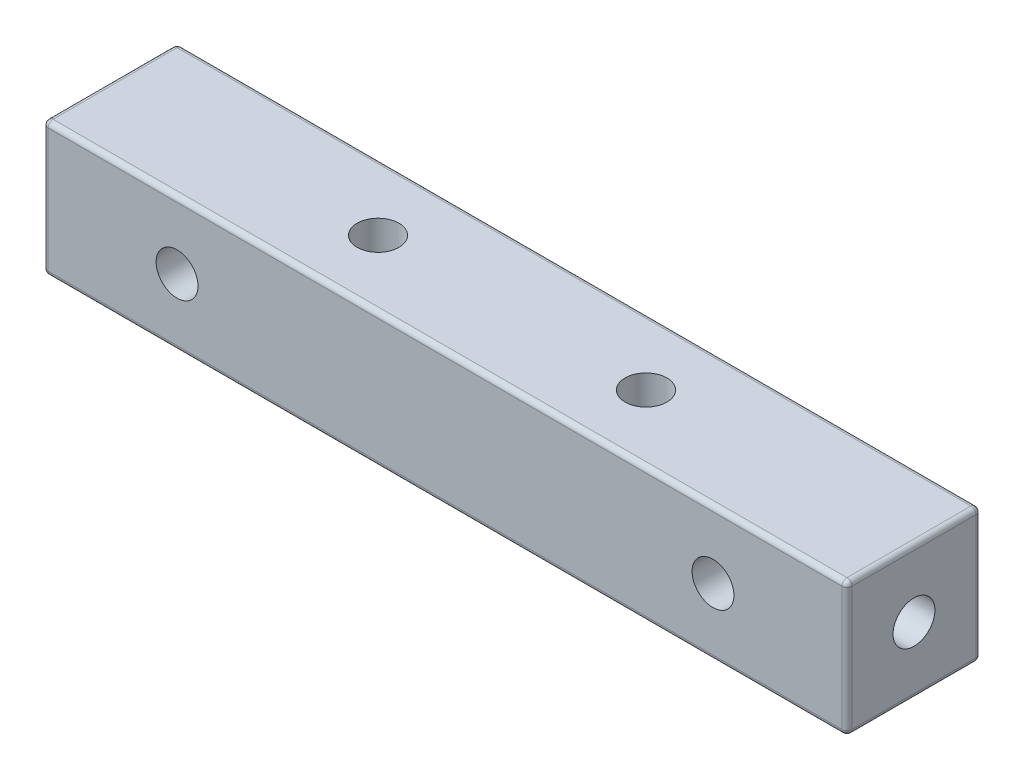
SolidWorks part; units mm, degrees
material "6061 合金"
ref_plane "前视基准面" through (0, 0, 0) normal (0, 0, 1) x (1, 0, 0)
ref_plane "上视基准面" through (0, 0, 0) normal (0, 1, 0) x (1, 0, 0)
ref_plane "右视基准面" through (0, 0, 0) normal (1, 0, 0) x (0, 0, -1)
sketch "草图1" plane through (0, 0, 0) normal (1, 0, 0) x (0, 0, -1)
  line L1 (-4, -4) -> (4, -4)
  line L2 (-4, -4) -> (-4, 4)
  line L3 (-4, 4) -> (4, 4)
  line L4 (4, -4) -> (4, 4)
  line L5 (0, 4) -> (0, -4) construction
  line L6 (-4, 0) -> (4, 0) construction
  point P0 (0, 0)
  dimension "D1" = 8
extrude "凸台-拉伸1" add sketch "草图1" along normal mid plane 48
sketch "草图2" plane through (0, 4, 0) normal (0, 1, 0) x (1, 0, 0)
  line L0 (-8, 0) -> (8, 0) construction
  circle A0 centre (8, 0) radius 1.25
  circle A1 centre (-8, 0) radius 1.25
  point P4 (0, 0)
  dimension "D2" = 2.5
  dimension "D1" = 16
sketch "草图3" plane through (0, 0, 4) normal (0, 0, 1) x (1, 0, 0)
  line L0 (-16, 0) -> (16, 0) construction
  circle A0 centre (16, 0) radius 1.25
  circle A1 centre (-16, 0) radius 1.25
  point P4 (0, 0)
  dimension "D2" = 2.5
  dimension "D1" = 32
sketch "草图4" plane through (24, 0, 0) normal (1, 0, 0) x (0, 0, -1)
  circle A0 centre (0, 0) radius 1.25
  dimension "D1" = 2.5
fillet "圆角1" radius 0.3 12 edges at (-24, -4, 0) (-24, 4, 0) (24, -4, 0) (24, 4, 0) (-24, 0, 4) (-24, 0, -4) (24, 0, -4) (24, 0, 4) (0, -4, -4) (0, 4, -4) (0, -4, 4) (0, 4, 4)
hole_wizard "螺纹孔1" positions "草图5" profile "草图6" tap size "M3" standard "GB" end condition through all
sketch "草图5" plane through (0, 4, 0) normal (0, 1, 0) x (1, 0, 0)
  point P0 (-8, 0)
  point P3 (8, 0)
sketch "草图6" plane through (-8, 4, 0) normal (1, 0, 0) x (0, 0, 1)
  line L0 (0, 0) -> (0, 8)
  line L1 (0, 8) -> (1.25, 8)
  line L2 (1.25, 8) -> (1.25, 0)
  line L5 (1.25, 0) -> (0, 0)
  line L11 (0, -6.35) -> (0, 107.95) construction
  dimension "通孔螺纹孔钻头直径" = 2.5
  dimension "通孔螺纹孔钻头深度" = 8
cosmetic thread "孔螺蚊线1" parameters "D2"=3.6
cosmetic thread "孔螺蚊线2" parameters "D2"=3.6
hole_wizard "螺纹孔2" positions "草图7" profile "草图8" tap size "M3" standard "GB" end condition through all
sketch "草图7" plane through (0, 0, 4) normal (0, 0, 1) x (1, 0, 0)
  point P0 (-16, 0)
  point P3 (16, 0)
sketch "草图8" plane through (-16, 0, 4) normal (1, 0, 0) x (0, -1, 0)
  line L0 (0, 0) -> (0, 8)
  line L1 (0, 8) -> (1.25, 8)
  line L2 (1.25, 8) -> (1.25, 0)
  line L5 (1.25, 0) -> (0, 0)
  line L11 (0, -6.35) -> (0, 107.95) construction
  dimension "通孔螺纹孔钻头直径" = 2.5
  dimension "通孔螺纹孔钻头深度" = 8
cosmetic thread "孔螺蚊线3" parameters "D2"=3.6
cosmetic thread "孔螺蚊线4" parameters "D2"=3.6
hole_wizard "螺纹孔3" positions "草图9" profile "草图10" tap size "M3" standard "GB"
sketch "草图9" plane through (-24, 0, 0) normal (-1, 0, 0) x (0, 0, 1)
  point P0 (0, 0)
sketch "草图10" plane through (-24, 0, 0) normal (0, 1, 0) x (0, 0, 1)
  line L0 (0, 0) -> (0, 6.75)
  line L1 (0, 6.75) -> (1.25, 6.75)
  line L2 (1.25, 6.75) -> (1.25, 0)
  line L5 (1.25, 0) -> (0, 0)
  line L11 (0, -6.35) -> (0, 107.95) construction
  dimension "通孔螺纹孔钻头直径" = 2.5
  dimension "通孔螺纹孔钻头深度" = 6.75
cosmetic thread "孔螺蚊线5" parameters "D2"=3.6
mirror "镜向1" about plane through (0, 0, 0) normal (1, 0, 0) of "螺纹孔3"
cosmetic thread "孔螺蚊线6" parameters "D2"=3.6
